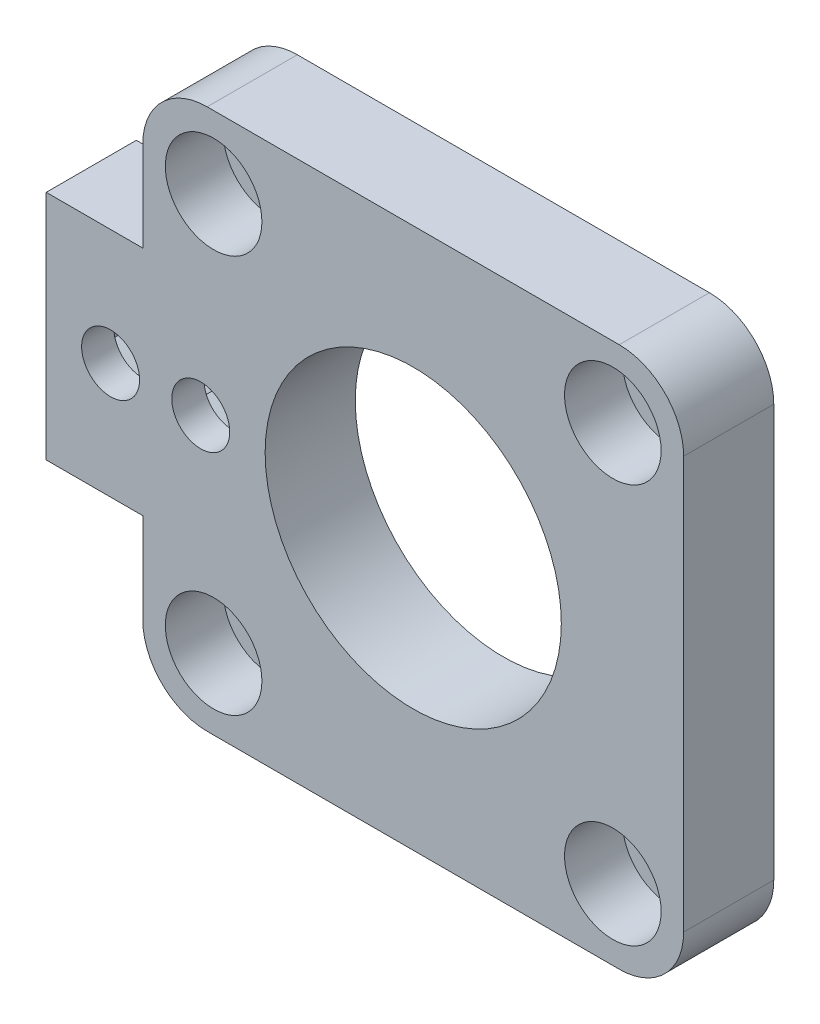
SolidWorks part; units mm, degrees
ref_plane "Plan de face" through (0, 0, 0) normal (0, 0, 1) x (1, 0, 0)
ref_plane "Plan de dessus" through (0, 0, 0) normal (0, 1, 0) x (1, 0, 0)
ref_plane "Plan de droite" through (0, 0, 0) normal (1, 0, 0) x (0, 0, -1)
sketch "Esquisse1" plane through (0, 0, 0) normal (0, 0, 1) x (1, 0, 0)
  line L1 (0, 0) -> (-42, 0)
  line L2 (0, 0) -> (0, -42)
  line L3 (0, -42) -> (-42, -42)
  line L4 (-42, 0) -> (-42, -42)
  line L5 (-42, -30) -> (-49.5, -30)
  line L6 (-42, -30) -> (-42, -12)
  line L7 (-42, -12) -> (-49.5, -12)
  line L8 (-49.5, -30) -> (-49.5, -12)
  circle A0 centre (-36.5, -5.611) radius 1.75
  circle A1 centre (-5.5, -5.5) radius 1.75
  circle A2 centre (-5.5, -36.5) radius 1.75
  circle A3 centre (-36.5, -36.5) radius 1.75
  circle A4 centre (-21, -21) radius 11.5
  dimension "D3" = 3.5
  dimension "D4" = 3.5
  dimension "D5" = 3.5
  dimension "D6" = 3.5
  dimension "D17" = 23
  dimension "D1" = 42
  dimension "D2" = 42
  dimension "D7" = 5.5
  dimension "D8" = 5.5
  dimension "D9" = 5.5
  dimension "D10" = 5.5
  dimension "D11" = 5.5
  dimension "D12" = 5.611
  dimension "D13" = 5.5
  dimension "D14" = 5.5
  dimension "D15" = 21
  dimension "D16" = 21
  dimension "D18" = 18
  dimension "D19" = 28.5
  dimension "D20" = 12
extrude "Boss.-Extru.1" add sketch "Esquisse1" along normal blind 7 contours L1 L4 L3 L2 A4 A3 A2 A1 A0 | L8 L5 L4 L7
sketch "Esquisse9" plane through (0, 0, 7) normal (0, 0, 1) x (1, 0, 0)
  line L0 (-42, -30) -> (-49.5, -30) construction
  line L1 (-49.5, -30) -> (-49.5, -12) construction
  circle A0 centre (-44.5, -21) radius 2.25
  circle A1 centre (-37.5, -21) radius 2.25
  dimension "D1" = 4.5
  dimension "D2" = 4.5
  dimension "D3" = 9
  dimension "D4" = 9
  dimension "D5" = 5
  dimension "D6" = 12
extrude "Enlèv. mat.-Extru.2" cut sketch "Esquisse9" against normal blind 17 contours A1 | A0
sketch "Esquisse10" plane through (0, 0, 0) normal (0, 0, -1) x (-1, 0, 0)
  line L0 (49.5, -30) -> (49.5, -12) construction
  line L1 (44.5, -25.3301) -> (48.25, -23.1651)
  line L2 (48.25, -23.1651) -> (48.25, -18.8349)
  line L3 (48.25, -18.8349) -> (44.5, -16.6699)
  line L4 (44.5, -16.6699) -> (40.75, -18.8349)
  line L5 (40.75, -18.8349) -> (40.75, -23.1651)
  line L6 (40.75, -23.1651) -> (44.5, -25.3301)
  line L7 (37.5, -25.3301) -> (41.25, -23.1651)
  line L8 (41.25, -23.1651) -> (41.25, -18.8349)
  line L9 (41.25, -18.8349) -> (37.5, -16.6699)
  line L10 (37.5, -16.6699) -> (33.75, -18.8349)
  line L11 (33.75, -18.8349) -> (33.75, -23.1651)
  line L12 (33.75, -23.1651) -> (37.5, -25.3301)
  circle A2 centre (44.5, -21) radius 3.75 construction
  circle A3 centre (37.5, -21) radius 3.75 construction
  dimension "D3" = 7.5
  dimension "D4" = 7.5
  dimension "D5" = 0
  dimension "D6" = 0
extrude "Enlèv. mat.-Extru.3" cut sketch "Esquisse10" against normal blind 4.5 contours L8 L9 L10 L11 L12 L7
sketch "Esquisse11" plane through (0, 0, 7) normal (0, 0, 1) x (1, 0, 0)
  circle A0 centre (-36.5, -5.611) radius 3.75
  circle A1 centre (-5.5, -5.5) radius 3.75
  circle A2 centre (-5.5, -36.5) radius 3.75
  circle A3 centre (-36.5, -36.5) radius 3.75
  dimension "D1" = 7.5
  dimension "D2" = 7.5
  dimension "D3" = 7.5
  dimension "D4" = 7.5
extrude "Enlèv. mat.-Extru.4" cut sketch "Esquisse11" against normal blind 4.5
fillet "Congé1" radius 5 4 edges at (-42, 0, 3.5) (0, 0, 3.5) (0, -42, 3.5) (-42, -42, 3.5)
